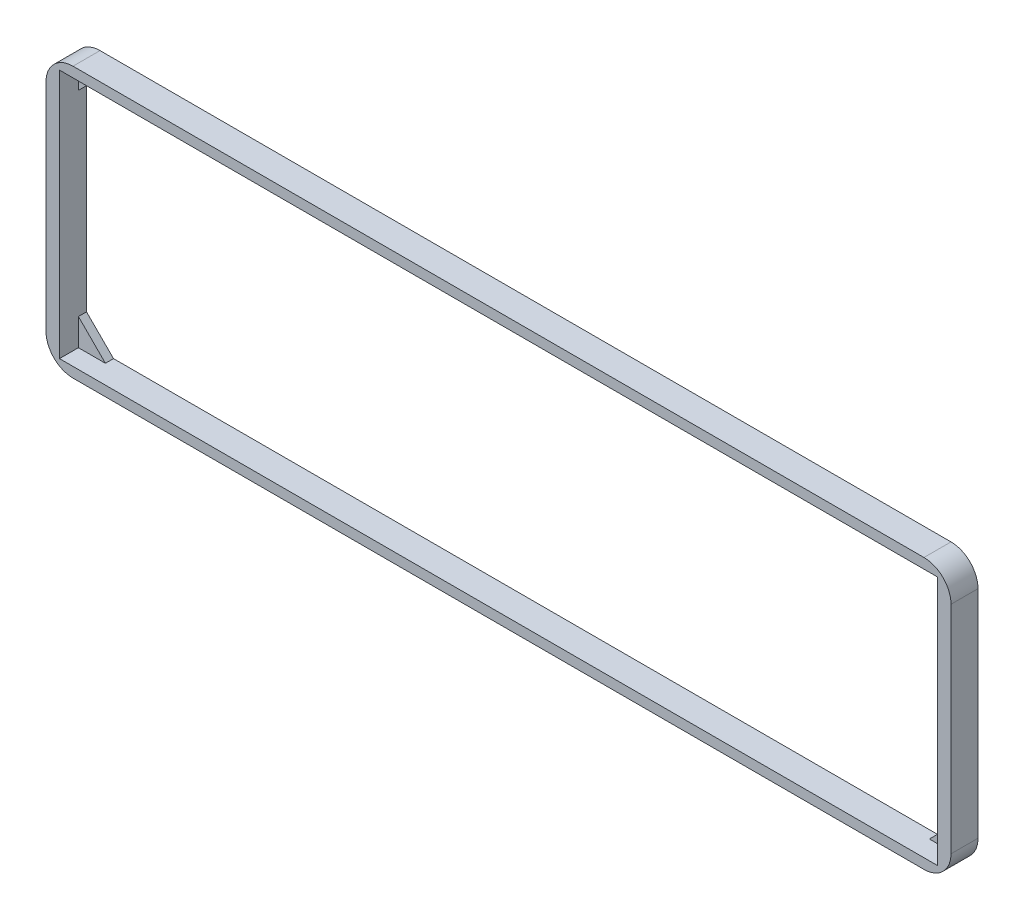
SolidWorks part; units mm, degrees
ref_plane "Front Plane" through (0, 0, 0) normal (0, 0, 1) x (1, 0, 0)
ref_plane "Top Plane" through (0, 0, 0) normal (0, 1, 0) x (1, 0, 0)
ref_plane "Right Plane" through (0, 0, 0) normal (1, 0, 0) x (0, 0, -1)
sketch "Sketch1" plane through (0, 0, 0) normal (0, 0, 1) x (1, 0, 0)
  line L1 (-167.5, -50) -> (167.5, -50)
  line L2 (-167.5, -50) -> (-167.5, 50)
  line L3 (-167.5, 50) -> (167.5, 50)
  line L4 (167.5, -50) -> (167.5, 50)
  line L5 (-167.5, -50) -> (167.5, 50) construction
  line L6 (-167.5, 50) -> (167.5, -50) construction
  line L7 (-162.5, -46.25) -> (162.5, -46.25)
  line L8 (-162.5, -46.25) -> (-162.5, 46.25)
  line L9 (-162.5, 46.25) -> (162.5, 46.25)
  line L10 (162.5, -46.25) -> (162.5, 46.25)
  line L11 (-162.5, -46.25) -> (162.5, 46.25) construction
  line L12 (-162.5, 46.25) -> (162.5, -46.25) construction
  point P0 (0, 0)
  point P6 (0, 0)
  dimension "D1" = 335
  dimension "D2" = 100
  dimension "D3" = 325
  dimension "D4" = 92.5
extrude "Boss-Extrude1" add sketch "Sketch1" against normal blind 10
fillet "Fillet1" radius 10 4 edges at (-167.5, 50, -5) (-167.5, -50, -5) (167.5, -50, -5) (167.5, 50, -5)
sketch "Sketch2" plane through (0, 0, -10) normal (0, 0, -1) x (-1, 0, 0)
  line L0 (-162.5, -46.25) -> (-162.5, -36.25)
  line L1 (-162.5, -46.25) -> (-162.5, 46.25) construction
  line L2 (-162.5, -36.25) -> (-152.5, -46.25)
  line L3 (162.5, -46.25) -> (-162.5, -46.25) construction
  line L4 (-152.5, -46.25) -> (-162.5, -46.25)
  line L5 (-162.5, 46.25) -> (-152.5, 46.25)
  line L6 (-162.5, 46.25) -> (162.5, 46.25) construction
  line L7 (-152.5, 46.25) -> (-162.5, 36.25)
  line L8 (-162.5, 36.25) -> (-162.5, 46.25)
  line L9 (162.5, 46.25) -> (152.5, 46.25)
  line L10 (152.5, 46.25) -> (162.5, 36.25)
  line L11 (162.5, 46.25) -> (162.5, -46.25) construction
  line L12 (162.5, 36.25) -> (162.5, 46.25)
  line L13 (162.5, -46.25) -> (162.5, -36.25)
  line L14 (162.5, -36.25) -> (152.5, -46.25)
  line L15 (152.5, -46.25) -> (162.5, -46.25)
  dimension "D1" = 10
  dimension "D2" = 10
  dimension "D3" = 10
  dimension "D4" = 10
  dimension "D5" = 10
  dimension "D6" = 10
  dimension "D7" = 10
  dimension "D8" = 10
extrude "Boss-Extrude2" add sketch "Sketch2" against normal blind 3
